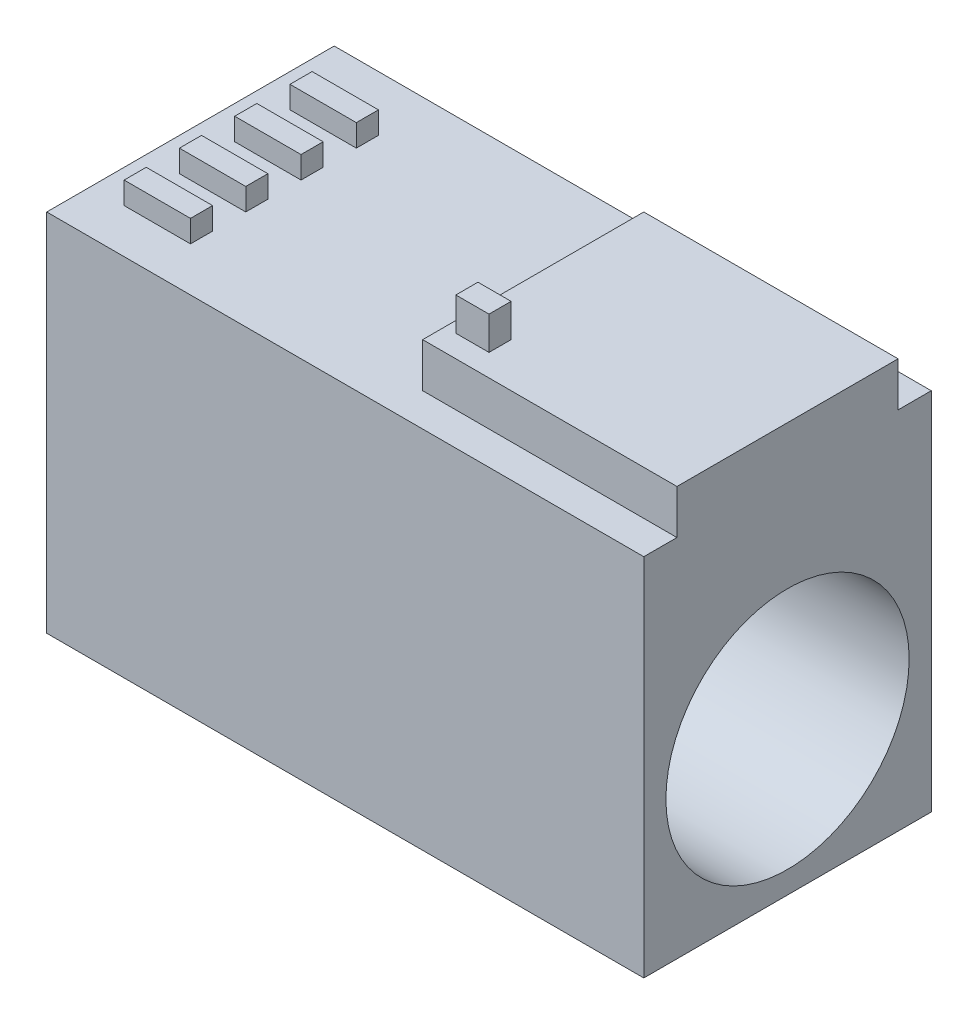
SolidWorks part; units mm, degrees
ref_plane "Płaszczyzna przednia" through (0, 0, 0) normal (0, 0, 1) x (1, 0, 0)
ref_plane "Płaszczyzna górna" through (0, 0, 0) normal (0, 1, 0) x (1, 0, 0)
ref_plane "Płaszczyzna prawa" through (0, 0, 0) normal (1, 0, 0) x (0, 0, -1)
sketch "Szkic1" plane through (0, 0, 0) normal (0, 0, 1) x (1, 0, 0)
  line L0 (135, 0) -> (-135, 0)
  line L1 (-135, 0) -> (-135, 165)
  line L2 (-135, 165) -> (20, 165)
  line L3 (20, 165) -> (20, 185)
  line L4 (20, 185) -> (135, 185)
  line L5 (135, 185) -> (135, 0)
  point P4 (0, 0)
  dimension "D1" = 270
  dimension "D2" = 185
  dimension "D3" = 165
  dimension "D4" = 115
extrude "Dodanie-wyciągnięcie1" add sketch "Szkic1" along normal blind 130
sketch "Szkic2" plane through (0, 185, 0) normal (0, 1, 0) x (1, 0, 0)
  line L0 (20, -130) -> (20, 0) construction
  line L1 (135, -130) -> (20, -130)
  line L2 (135, -130) -> (135, -115)
  line L3 (135, -115) -> (20, -115)
  line L4 (20, -130) -> (20, -115)
  line L5 (20, -130) -> (20, 0) construction
  line L6 (135, 0) -> (20, 0)
  line L7 (135, 0) -> (135, -15)
  line L8 (135, -15) -> (20, -15)
  line L9 (20, 0) -> (20, -15)
  dimension "D1" = 15
  dimension "D2" = 15
extrude "Wytnij-wyciągnięcie1" cut sketch "Szkic2" against normal up to surface (20 mm away) up to face at (-57.5, 165, 65)
sketch "Szkic3" plane through (0, 165, 0) normal (0, 1, 0) x (1, 0, 0)
  line L0 (135, -130) -> (-135, -130) construction
  line L1 (-120, -110) -> (-90, -110)
  line L2 (-120, -110) -> (-120, -100)
  line L3 (-120, -100) -> (-90, -100)
  line L4 (-90, -110) -> (-90, -100)
  line L5 (-135, -130) -> (-135, 0) construction
  line L6 (-120, -85) -> (-120, -75)
  line L7 (-120, -85) -> (-90, -85)
  line L8 (-90, -85) -> (-90, -75)
  line L9 (-120, -75) -> (-90, -75)
  line L10 (-120, -60) -> (-120, -50)
  line L11 (-120, -60) -> (-90, -60)
  line L12 (-90, -60) -> (-90, -50)
  line L13 (-120, -50) -> (-90, -50)
  line L14 (-120, -35) -> (-120, -25)
  line L15 (-120, -35) -> (-90, -35)
  line L16 (-90, -35) -> (-90, -25)
  line L17 (-120, -25) -> (-90, -25)
  dimension "D1" = 10
  dimension "D2" = 20
  dimension "D3" = 15
  dimension "D4" = 30
  dimension "D5" = 4
extrude "Dodanie-wyciągnięcie2" add sketch "Szkic3" along normal blind 10
sketch "Szkic4" plane through (0, 185, 0) normal (0, 1, 0) x (1, 0, 0)
  line L0 (135, -130) -> (-135, -130) construction
  line L1 (25, -105) -> (40, -105)
  line L2 (25, -105) -> (25, -95)
  line L3 (25, -95) -> (40, -95)
  line L4 (40, -105) -> (40, -95)
  line L5 (20, -115) -> (20, -15) construction
  dimension "D1" = 15
  dimension "D2" = 10
  dimension "D3" = 25
  dimension "D4" = 5
extrude "Dodanie-wyciągnięcie3" add sketch "Szkic4" along normal blind 15
sketch "Szkic5" plane through (-135, 0, 0) normal (-1, 0, 0) x (0, 0, 1)
  line L0 (130, 0) -> (0, 0) construction
  circle A0 centre (65, 65) radius 55
  point P4 (65, 0)
  dimension "D1" = 110
  dimension "D2" = 65
extrude "Wytnij-wyciągnięcie2" cut sketch "Szkic5" against normal through all
